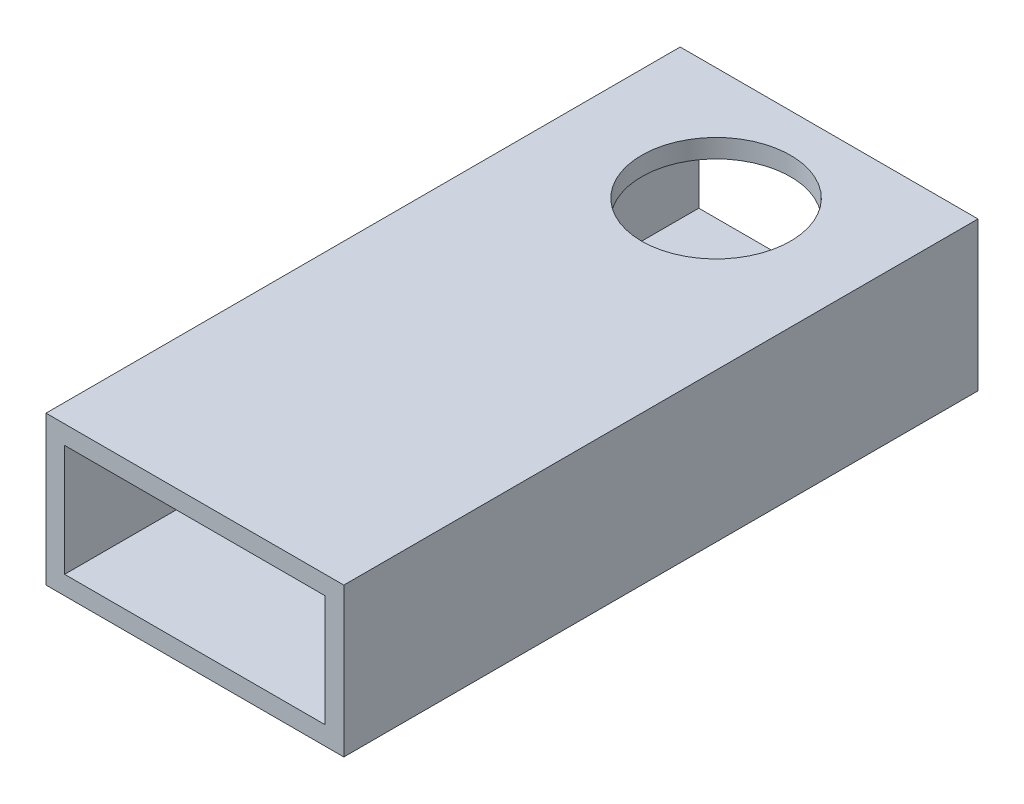
SolidWorks part; units mm, degrees
material "6061 Alloy"
ref_plane "Front Plane" through (0, 0, 0) normal (0, 0, 1) x (1, 0, 0)
ref_plane "Top Plane" through (0, 0, 0) normal (0, 1, 0) x (1, 0, 0)
ref_plane "Right Plane" through (0, 0, 0) normal (1, 0, 0) x (0, 0, -1)
sketch "Sketch1" plane through (0, 0, 0) normal (0, 0, 1) x (1, 0, 0)
  line L1 (0, 0) -> (50.8, 0)
  line L2 (0, 0) -> (0, -25.4)
  line L3 (0, -25.4) -> (50.8, -25.4)
  line L4 (50.8, 0) -> (50.8, -25.4)
extrude "Boss-Extrude1" add sketch "Sketch1" along normal blind 108.1786
sketch "Sketch2" plane through (0, 0, 108.1786) normal (0, 0, 1) x (1, 0, 0)
  line L0 (0, 0) -> (0, -25.4) construction
  line L1 (3.175, -3.175) -> (47.625, -3.175)
  line L2 (3.175, -3.175) -> (3.175, -22.225)
  line L3 (3.175, -22.225) -> (47.625, -22.225)
  line L4 (47.625, -3.175) -> (47.625, -22.225)
  line L5 (50.8, 0) -> (0, 0) construction
  line L6 (0, -25.4) -> (50.8, -25.4) construction
  line L7 (50.8, -25.4) -> (50.8, 0) construction
  dimension "D1" = 3.175
  dimension "D2" = 3.175
  dimension "D3" = 3.175
  dimension "D4" = 3.175
extrude "Cut-Extrude1" cut sketch "Sketch2" against normal through all
sketch "Sketch3" plane through (0, 0, 0) normal (0, 1, 0) x (1, 0, 0)
  line L0 (50.8, -108.1786) -> (0, -108.1786) construction
  circle A0 centre (25.4, -19.2786) radius 12.7
  dimension "D1" = 88.9
  dimension "D2" = 25.4
extrude "Cut-Extrude2" cut sketch "Sketch3" against normal blind 3.175
sketch "Sketch5" plane through (0, -25.4, 0) normal (0, -1, 0) x (1, 0, 0)
  line L0 (0, 108.1786) -> (50.8, 108.1786) construction
  circle A0 centre (25.4, 19.2786) radius 6.35
  dimension "D1" = 12.7
  dimension "D2" = 88.9
extrude "Cut-Extrude3" cut sketch "Sketch5" against normal blind 108.1786
